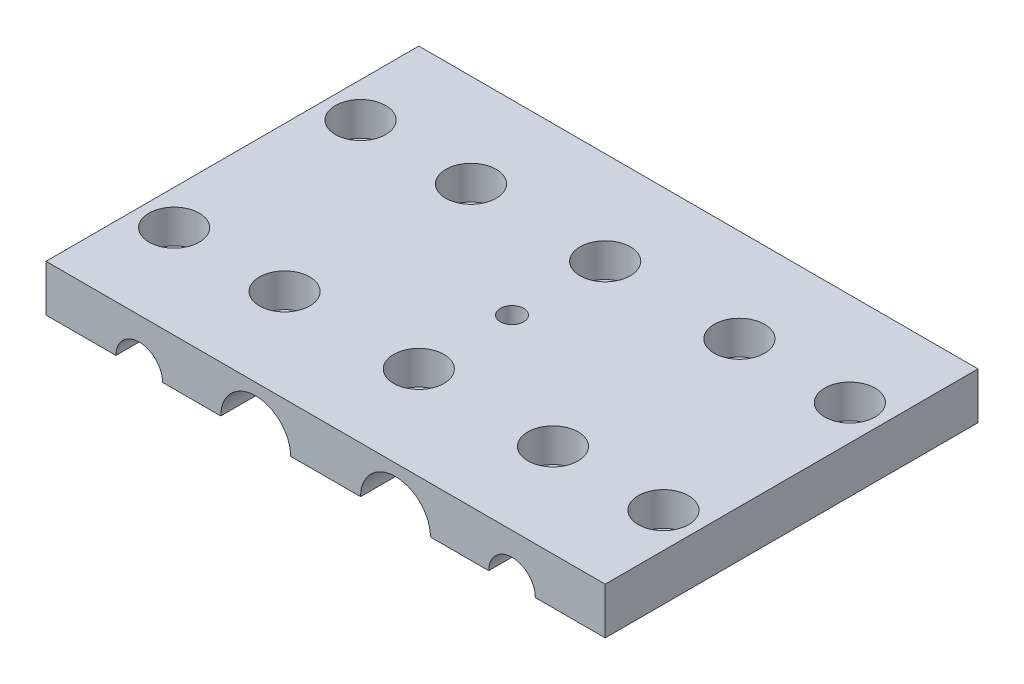
SolidWorks part; units mm, degrees
material "Copper"
ref_plane "Front Plane" through (0, 0, 0) normal (0, 0, 1) x (1, 0, 0)
ref_plane "Top Plane" through (0, 0, 0) normal (0, 1, 0) x (1, 0, 0)
ref_plane "Right Plane" through (0, 0, 0) normal (1, 0, 0) x (0, 0, -1)
sketch "Sketch1" plane through (0, 0, 0) normal (0, 1, 0) x (1, 0, 0)
  line L1 (-38.1, 25.4) -> (38.1, 25.4)
  line L2 (-38.1, 25.4) -> (-38.1, -25.4)
  line L3 (-38.1, -25.4) -> (38.1, -25.4)
  line L4 (38.1, 25.4) -> (38.1, -25.4)
  dimension "D1" = 50.8
  dimension "D2" = 76.2
  dimension "D3" = 38.1
  dimension "D4" = 25.4
extrude "Boss-Extrude1" add sketch "Sketch1" along normal blind 6.35
sketch "Sketch2" plane through (0, 0, 25.4) normal (0, 0, 1) x (1, 0, 0)
  line L0 (-38.1, 0) -> (38.1, 0) construction
  line L1 (-38.1, 6.35) -> (-38.1, 0) construction
  circle A0 centre (-25.4, 0) radius 3.175
  circle A1 centre (25.4, 0) radius 3.175
  dimension "D3" = 6.35
  dimension "D1" = 50.8
  dimension "D2" = 12.7
extrude "Cut-Extrude1" cut sketch "Sketch2" against normal through all
sketch "Sketch3" plane through (0, 0, 25.4) normal (0, 0, 1) x (1, 0, 0)
  line L0 (-22.225, 0) -> (22.225, 0) construction
  circle A0 centre (-9.525, 0) radius 4.7625
  circle A1 centre (9.525, 0) radius 4.7625
  dimension "D1" = 9.525
  dimension "D2" = 19.05
  dimension "D3" = 9.525
extrude "Cut-Extrude2" cut sketch "Sketch3" against normal through all
hole_wizard "#8 Clearance Hole1" positions "Sketch5" profile "Sketch4" hole size "#8" standard "ANSI Inch" end condition through all
sketch "Sketch5" plane through (0, 6.35, 0) normal (0, 1, 0) x (1, 0, 0)
  line L2 (38.1, 25.4) -> (-38.1, 25.4) construction
  line L3 (-38.1, -25.4) -> (38.1, -25.4) construction
  line L4 (-38.1, 25.4) -> (-38.1, -25.4) construction
  line L5 (38.1, -25.4) -> (38.1, 25.4) construction
  point P0 (-33.3375, 12.7)
  point P2 (-33.3375, -12.7)
  point P4 (-18.288, -12.7)
  point P6 (0, -12.7)
  point P8 (18.288, -12.7)
  point P10 (33.3375, -12.7)
  point P12 (33.3375, 12.7)
  point P14 (18.288, 12.7)
  point P16 (0, 12.7)
  point P18 (-18.288, 12.7)
  dimension "D1" = 12.7
  dimension "D2" = 12.7
  dimension "D3" = 4.7625
  dimension "D4" = 4.7625
  dimension "D5" = 19.812
  dimension "D6" = 19.812
sketch "Sketch4" plane through (-33.3375, 6.35, -12.7) normal (1, 0, 0) x (0, 0, 1)
  line L0 (0, 0) -> (0, 6.35)
  line L1 (0, 6.35) -> (2.2479, 6.35)
  line L2 (2.2479, 6.35) -> (2.2479, 0)
  line L5 (2.2479, 0) -> (0, 0)
  line L11 (0, -6.35) -> (0, 107.95) construction
  dimension "Thru Hole Dia." = 4.4958
  dimension "Thru Hole Depth" = 6.35
sketch "Sketch6" plane through (0, 6.35, 0) normal (0, 1, 0) x (1, 0, 0)
  circle A0 centre (-33.3375, 12.7) radius 3.429
  circle A1 centre (-18.288, 12.7) radius 3.429
  circle A2 centre (0, 12.7) radius 3.429
  circle A3 centre (18.288, 12.7) radius 3.429
  circle A4 centre (33.3375, 12.7) radius 3.429
  circle A5 centre (33.3375, -12.7) radius 3.429
  circle A6 centre (18.288, -12.7) radius 3.429
  circle A7 centre (0, -12.7) radius 3.429
  circle A8 centre (-18.288, -12.7) radius 3.429
  circle A9 centre (-33.3375, -12.7) radius 3.429
  dimension "D1" = 6.858
extrude "Cut-Extrude3" cut sketch "Sketch6" against normal blind 4.572
sketch "Sketch7" plane through (0, 6.35, 0) normal (0, 1, 0) x (1, 0, 0)
  circle A0 centre (0, 0) radius 1.5875
  dimension "D1" = 3.175
extrude "Cut-Extrude4" cut sketch "Sketch7" against normal through all
